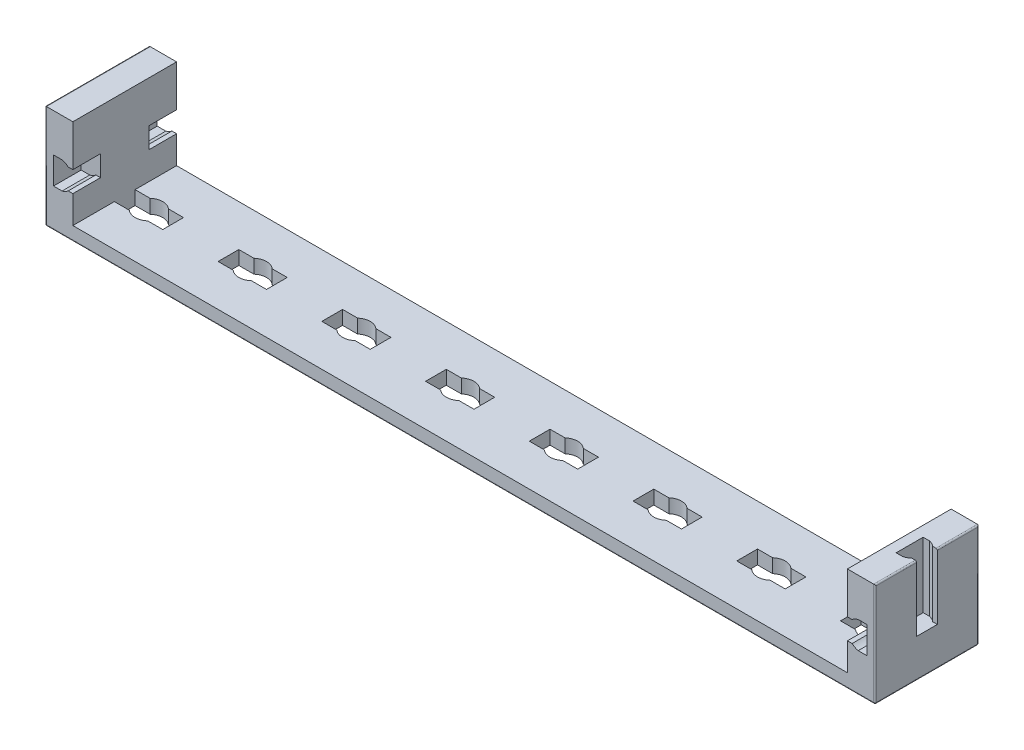
SolidWorks part; units mm, degrees
ref_plane "前视基准面" through (0, 0, 0) normal (0, 0, 1) x (1, 0, 0)
ref_plane "上视基准面" through (0, 0, 0) normal (0, 1, 0) x (1, 0, 0)
ref_plane "右视基准面" through (0, 0, 0) normal (1, 0, 0) x (0, 0, -1)
sketch "草图1" plane through (0, 0, 0) normal (0, 1, 0) x (1, 0, 0)
  line L0 (60, 7.5) -> (60, -7.5)
  line L1 (60, 7.5) -> (-60, 7.5)
  line L2 (60, -7.5) -> (-60, -7.5)
  line L3 (-60, 7.5) -> (-60, -7.5)
  line L4 (60, 7.5) -> (-60, -7.5) construction
  line L5 (60, -7.5) -> (-60, 7.5) construction
  point P1 (0, 0)
  dimension "D1" = 120
  dimension "D2" = 15
extrude "凸台-拉伸1" add sketch "草图1" along normal blind 2
sketch "草图2" plane through (0, 2, 0) normal (0, 1, 0) x (1, 0, 0)
  line L0 (-60, -7.5) -> (60, -7.5) construction
  line L1 (-60, 7.5) -> (-56, 7.5)
  line L2 (-60, 7.5) -> (-60, -7.5)
  line L3 (-60, -7.5) -> (-56, -7.5)
  line L4 (-56, 7.5) -> (-56, -7.5)
  line L6 (60, 7.5) -> (56, 7.5)
  line L7 (60, 7.5) -> (60, -7.5)
  line L8 (60, -7.5) -> (56, -7.5)
  line L9 (56, 7.5) -> (56, -7.5)
  dimension "D1" = 4
  dimension "D2" = 4
extrude "凸台-拉伸2" add sketch "草图2" along normal blind 13
sketch "草图3" plane through (0, 2, 0) normal (0, 1, 0) x (1, 0, 0)
  line L0 (0, 0) -> (-7.5, 0) construction
  line L1 (-4, -1.5) -> (-4, 1.5)
  line L2 (-4, -1.5) -> (-6.1771, -1.5)
  line L3 (-4, 1.5) -> (-6.1771, 1.5)
  line L4 (-11, -1.5) -> (-11, 1.5)
  line L5 (-4, -1.5) -> (-11, 1.5) construction
  line L6 (-4, 1.5) -> (-11, -1.5) construction
  line L7 (-8.8229, 1.5) -> (-11, 1.5)
  line L8 (-8.8229, -1.5) -> (-11, -1.5)
  arc A0 (-8.8229, -1.5) -> (-6.1771, -1.5) centre (-7.5, 0) ccw
  arc A1 (-6.1771, 1.5) -> (-8.8229, 1.5) centre (-7.5, 0) ccw
  dimension "D2" = 4
  dimension "D1" = 7.5
  dimension "D3" = 3
  dimension "D4" = 7
extrude "切除-拉伸1" cut sketch "草图3" against normal up to next
pattern_linear "阵列(线性)1" count 5 spacing 15 along (1, 0, 0) count 4 spacing 15 along (-1, 0, 0) of "切除-拉伸1"
sketch "草图4" plane through (0, 0, 7.5) normal (0, 0, 1) x (1, 0, 0)
  line L0 (-56, 2) -> (-56, 7.5) construction
  line L1 (-56, 15) -> (-56, 2) construction
  line L2 (-56, 7.5) -> (-58, 7.5) construction
  line L3 (-58, 7.5) -> (-58.8, 7.5) construction
  line L4 (-56, 6) -> (-56, 9)
  line L5 (-56, 9) -> (-56.6771, 9)
  line L6 (-58.8, 5.55) -> (-58.8, 9.45)
  line L7 (-58.8, 9.45) -> (-57.5556, 9.45)
  line L8 (-56, 6) -> (-56.6771, 6)
  line L9 (-58.8, 5.55) -> (-57.5556, 5.55)
  arc A0 (-56.6771, 9) -> (-57.5556, 9.45) centre (-58, 7.5) ccw
  arc A1 (-56.6771, 6) -> (-57.5556, 5.55) centre (-58, 7.5) cw
  dimension "D6" = 2
  dimension "D1" = 5.5
  dimension "D2" = 2
  dimension "D3" = 0.8
  dimension "D4" = 1.5
  dimension "D5" = 1.95
extrude "切除-拉伸2" cut sketch "草图4" against normal blind 4
mirror "镜向1" about plane through (0, 0, 0) normal (0, 0, 1) of "切除-拉伸2"
mirror "镜向2" about plane through (0, 0, 0) normal (1, 0, 0) of "切除-拉伸2", "镜向1"
sketch "草图5" plane through (0, 15, 0) normal (0, 1, 0) x (1, 0, 0)
  line L0 (60, 0) -> (58, 0) construction
  line L1 (60, -7.5) -> (60, 7.5) construction
  line L2 (58, 0) -> (57.5, 0) construction
  line L3 (60, -1.5) -> (60, 1.5)
  line L4 (60, 1.5) -> (59.3229, 1.5)
  line L5 (57.5, -1.95) -> (57.5, 1.95)
  line L6 (57.5, 1.95) -> (58.4444, 1.95)
  line L7 (60, -1.5) -> (59.3229, -1.5)
  line L8 (57.5, -1.95) -> (58.4444, -1.95)
  arc A0 (59.3229, 1.5) -> (58.4444, 1.95) centre (58, 0) ccw
  arc A1 (59.3229, -1.5) -> (58.4444, -1.95) centre (58, 0) cw
  dimension "D5" = 2
  dimension "D1" = 2
  dimension "D2" = 0.5
  dimension "D3" = 1.5
  dimension "D4" = 1.95
extrude "切除-拉伸3" cut sketch "草图5" against normal blind 9.45
sketch "草图6" plane through (0, 15, 0) normal (0, 1, 0) x (1, 0, 0)
  line L0 (-60, 0) -> (-62, 0) construction
  line L1 (-60, 7.5) -> (-60, -7.5) construction
  line L2 (-62, 0) -> (-62.5, 0) construction
  line L3 (-60, -1.5) -> (-60, 1.5)
  line L4 (-60, 1.5) -> (-60.6771, 1.5)
  line L5 (-62.5, -1.95) -> (-62.5, 1.95)
  line L6 (-62.5, 1.95) -> (-61.5556, 1.95)
  line L7 (-60, -1.5) -> (-60.6771, -1.5)
  line L8 (-62.5, -1.95) -> (-61.5556, -1.95)
  arc A0 (-60.6771, 1.5) -> (-61.5556, 1.95) centre (-62, 0) ccw
  arc A1 (-60.6771, -1.5) -> (-61.5556, -1.95) centre (-62, 0) cw
  dimension "D5" = 2
  dimension "D1" = 2
  dimension "D2" = 0.5
  dimension "D3" = 1.5
  dimension "D4" = 1.95
extrude "凸台-拉伸3" add sketch "草图6" against normal blind 15
sketch "草图7" plane through (0, 0, 7.5) normal (0, 0, 1) x (1, 0, 0)
  line L0 (-60, 7.5) -> (-62, 7.5) construction
  line L1 (-60, 0) -> (-60, 15) construction
  line L2 (-62, 7.5) -> (-62.5, 7.5) construction
  line L3 (-62.5, 7.5) -> (-62.5, 9.45) construction
  line L4 (-62.5, 0) -> (-62.5, 15) construction
  line L5 (-62.5, 9.45) -> (-61.5556, 9.45)
  line L6 (-60, 7.5) -> (-60, 9) construction
  line L7 (-60, 15) -> (-60, 0) construction
  line L8 (-60, 9) -> (-60.6771, 9)
  line L9 (-62.5, 9.45) -> (-62.5, 15)
  line L10 (-62.5, 15) -> (-60, 15)
  line L11 (-60, 15) -> (-60, 9)
  line L12 (-60, 0) -> (-60, 6)
  line L13 (-62.5, 0) -> (-60, 0)
  line L14 (-62.5, 5.55) -> (-62.5, 0)
  line L15 (-60, 6) -> (-60.6771, 6)
  line L16 (-62.5, 5.55) -> (-61.5556, 5.55)
  arc A0 (-60.6771, 9) -> (-61.5556, 9.45) centre (-62, 7.5) ccw
  arc A1 (-60.6771, 6) -> (-61.5556, 5.55) centre (-62, 7.5) cw
  dimension "D5" = 2
  dimension "D1" = 2
  dimension "D2" = 0.5
  dimension "D3" = 1.5
  dimension "D4" = 1.95
extrude "切除-拉伸4" cut sketch "草图7" against normal blind 15
fillet "圆角1" radius 0.2 11 edges at (60, 15, -4.5) (60, 7.5, -7.5) (60, 7.5, 7.5) (60, 15, 4.5) (60, 0, 0) (0, 0, -7.5) (0, 0, 7.5) (-60, 7.5, 7.5) (-60, 7.5, -7.5)
fillet "圆角2" radius 0.1 4 edges at (-62.5, 7.5, 1.95) (-62.5, 5.55, 0) (-62.5, 7.5, -1.95) (-62.5, 9.45, 0)
